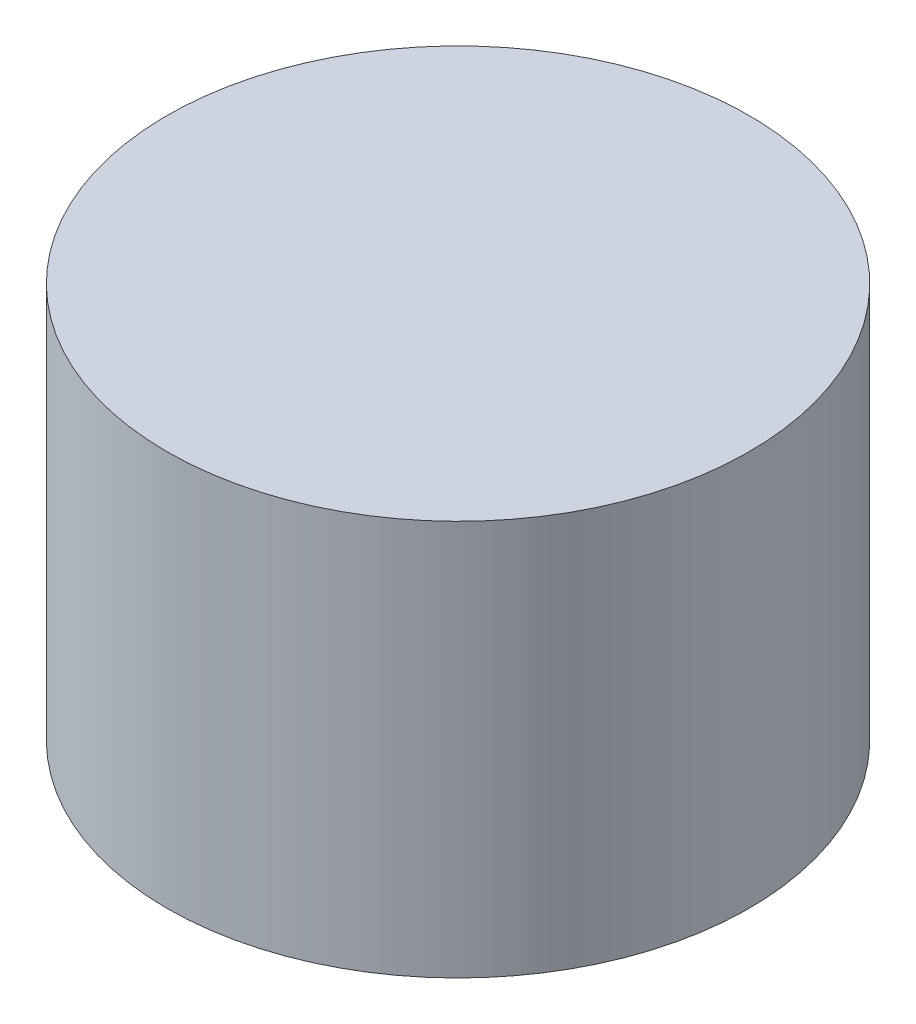
SolidWorks part; units mm, degrees
ref_plane "Plan de face" through (0, 0, 0) normal (0, 0, 1) x (1, 0, 0)
ref_plane "Plan de dessus" through (0, 0, 0) normal (0, 1, 0) x (1, 0, 0)
ref_plane "Plan de droite" through (0, 0, 0) normal (1, 0, 0) x (0, 0, -1)
sketch "Esquisse1" plane through (0, 0, 0) normal (0, 1, 0) x (1, 0, 0)
  circle A0 centre (0, 0) radius 73.61
  dimension "D1" = 147.22
extrude "Boss.-Extru.1" add sketch "Esquisse1" along normal blind 100
